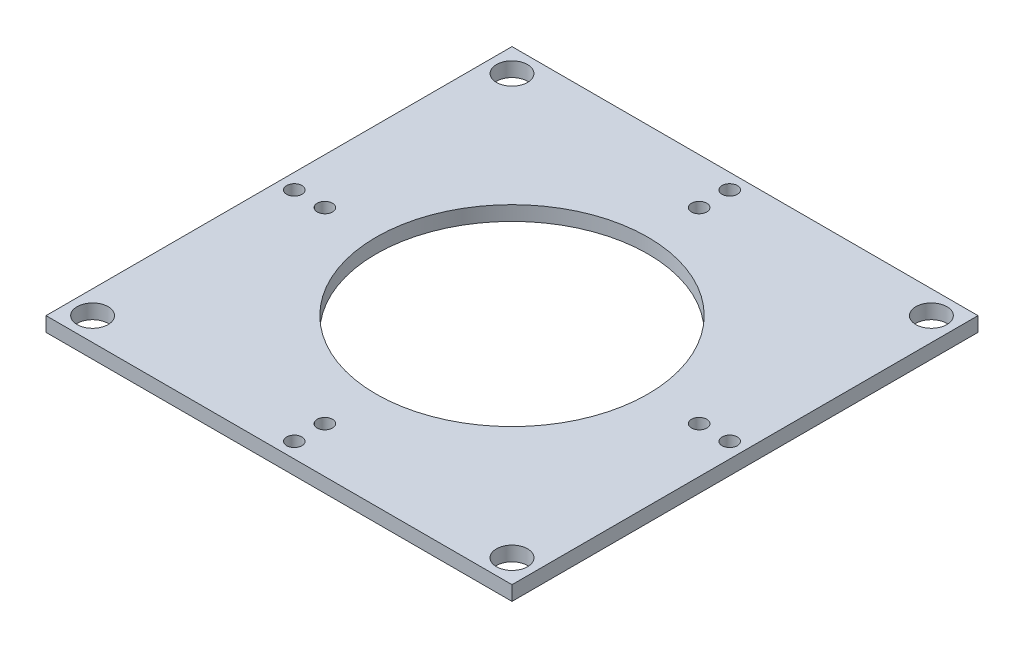
SolidWorks part; units mm, degrees
ref_plane "Front Plane" through (0, 0, 0) normal (0, 0, 1) x (1, 0, 0)
ref_plane "Top Plane" through (0, 0, 0) normal (0, 1, 0) x (1, 0, 0)
ref_plane "Right Plane" through (0, 0, 0) normal (1, 0, 0) x (0, 0, -1)
sketch "Sketch1" plane through (0, 0, 0) normal (0, 1, 0) x (1, 0, 0)
  line L0 (0, 0) -> (0, -76.2) construction
  line L1 (-76.2, 76.2) -> (76.2, 76.2)
  line L2 (-76.2, 76.2) -> (-76.2, -76.2)
  line L3 (-76.2, -76.2) -> (76.2, -76.2)
  line L4 (76.2, 76.2) -> (76.2, -76.2)
  line L5 (-76.2, 76.2) -> (-76.2, -76.2)
  line L6 (76.2, 76.2) -> (-76.2, 76.2)
  line L7 (76.2, -76.2) -> (76.2, 76.2)
  line L8 (0, 0) -> (76.2, 0) construction
  circle A0 centre (0, 0) radius 44.45
  circle A1 centre (0, -71.2) radius 2.5
  circle A2 centre (0, -61.2) radius 2.5
  circle A9 centre (-61.2, 0) radius 2.5
  circle A10 centre (-71.2, 0) radius 2.5
  circle A11 centre (0, 61.2) radius 2.5
  circle A12 centre (0, 71.2) radius 2.5
  circle A13 centre (61.2, 0) radius 2.5
  circle A14 centre (71.2, 0) radius 2.5
  circle A15 centre (-68.58, -68.58) radius 5.08
  circle A16 centre (-68.58, 68.58) radius 5.08
  circle A17 centre (68.58, 68.58) radius 5.08
  circle A18 centre (68.58, -68.58) radius 5.08
  point P8 (0, 76.2)
  point P9 (76.2, 0)
  point P13 (-71.2, -71.2)
  point P16 (-67.6856, -68.8506)
  point P34 (0, 0)
  point P35 (0, 0)
  point P44 (0, 0)
  dimension "D1" = 88.9
  dimension "D5" = 5
  dimension "D6" = 5
  dimension "D9" = 10.16
  dimension "D2" = 152.4
  dimension "D3" = 152.4
  dimension "D4" = 10
  dimension "D7" = 5
  dimension "D11" = 7.62
  dimension "D12" = 7.62
  dimension "D8" = 4
  dimension "D10" = 4
extrude "Boss-Extrude1" add sketch "Sketch1" along normal blind 4.7498
equation "\"D6@Sketch1\"=\"D5@Sketch1\""
equation "\"D3@Sketch1\"=\"D2@Sketch1\""
equation "\"D12@Sketch1\"=\"D11@Sketch1\""
